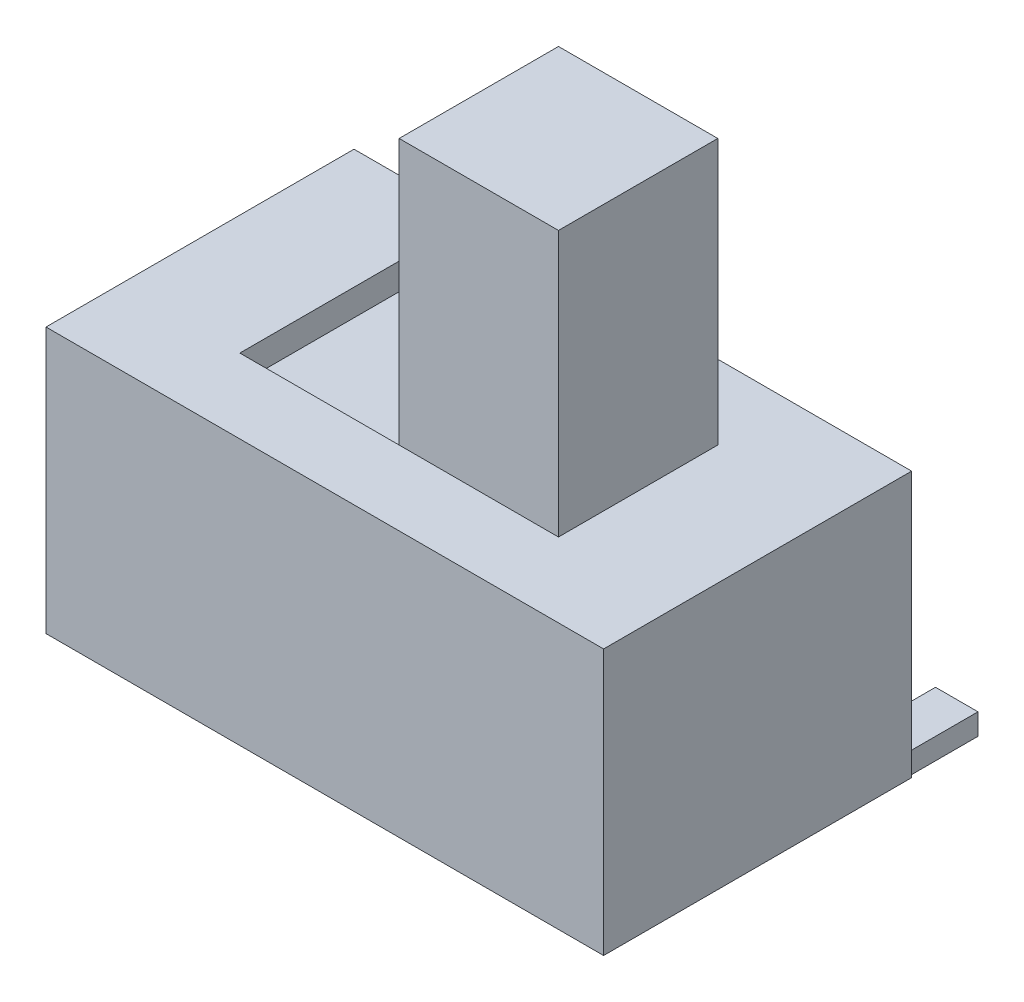
SolidWorks part; units mm, degrees
ref_plane "Front Plane" through (0, 0, 0) normal (0, 0, 1) x (1, 0, 0)
ref_plane "Top Plane" through (0, 0, 0) normal (0, 1, 0) x (1, 0, 0)
ref_plane "Right Plane" through (0, 0, 0) normal (1, 0, 0) x (0, 0, -1)
sketch "Sketch1" plane through (0, 0, 0) normal (0, 0, 1) x (1, 0, 0)
  line L1 (-5.25, 5) -> (5.25, 5)
  line L2 (-5.25, 5) -> (-5.25, 0)
  line L3 (-5.25, 0) -> (5.25, 0)
  line L4 (5.25, 5) -> (5.25, 0)
  dimension "D1" = 10.5
  dimension "D2" = 5
extrude "Boss-Extrude1" add sketch "Sketch1" along normal blind 5.8
sketch "Sketch2" plane through (0, 5, 0) normal (0, 1, 0) x (1, 0, 0)
  line L0 (0, 0) -> (0, -1.4) construction
  line L1 (-3, -1.4) -> (3, -1.4)
  line L2 (-3, -1.4) -> (-3, -4.4)
  line L3 (-3, -4.4) -> (3, -4.4)
  line L4 (3, -1.4) -> (3, -4.4)
  line L5 (3, -2.9) -> (5.25, -2.9) construction
  line L6 (5.25, -5.8) -> (5.25, 0) construction
  dimension "D1" = 6
  dimension "D2" = 3
extrude "Cut-Extrude1" cut sketch "Sketch2" against normal blind 0.5
sketch "Sketch3" plane through (0, 4.5, 0) normal (0, 1, 0) x (1, 0, 0)
  line L0 (-3, -4.4) -> (3, -4.4) construction
  line L1 (3, -1.4) -> (0, -1.4)
  line L2 (3, -1.4) -> (3, -4.4)
  line L3 (3, -4.4) -> (0, -4.4)
  line L4 (0, -1.4) -> (0, -4.4)
  dimension "D1" = 3
extrude "Boss-Extrude2" add sketch "Sketch3" along normal offset from surface (5.5 mm away) 5 up to face at (0, 5, 2.9) offset beyond the face yes
sketch "Sketch4" plane through (0, 0, 0) normal (1, 0, 0) x (0, 0, -1)
  line L0 (-2.7, 0) -> (-2.7, -0.8)
  line L1 (-5.8, 0) -> (0, 0) construction
  line L2 (-2.7, 0) -> (-3.1, 0)
  line L3 (-2.1, -1.4) -> (3.1, -1.4)
  line L4 (3.1, -1.4) -> (3.1, -1.8)
  line L5 (3.1, -1.8) -> (-2.1, -1.8)
  line L6 (-3.1, 0) -> (-3.1, -0.8)
  line L7 (3.1, -1.6) -> (-4.2397, -1.6) construction
  line L9 (-3.1, -0.8) -> (-2.7, -0.8) construction
  line L11 (-5.8, 5) -> (0, 5) construction
  arc A0 (-2.7, -0.8) -> (-2.1, -1.4) centre (-2.1, -0.8) ccw
  arc A1 (-3.1, -0.8) -> (-2.1, -1.8) centre (-2.1, -0.8) ccw
  point P4 (-2.9, 0)
  dimension "D3" = 0.6
  dimension "D1" = 0.4
  dimension "D2" = 6.8
  dimension "D4" = 6.2
  dimension "D5" = 1.6
extrude "Boss-Extrude3" add sketch "Sketch4" along normal mid plane 0.8
pattern_linear "LPattern1" count 2 spacing 3 along (-1, 0, 0) count 2 spacing 3 along (1, 0, 0) of "Boss-Extrude3"
